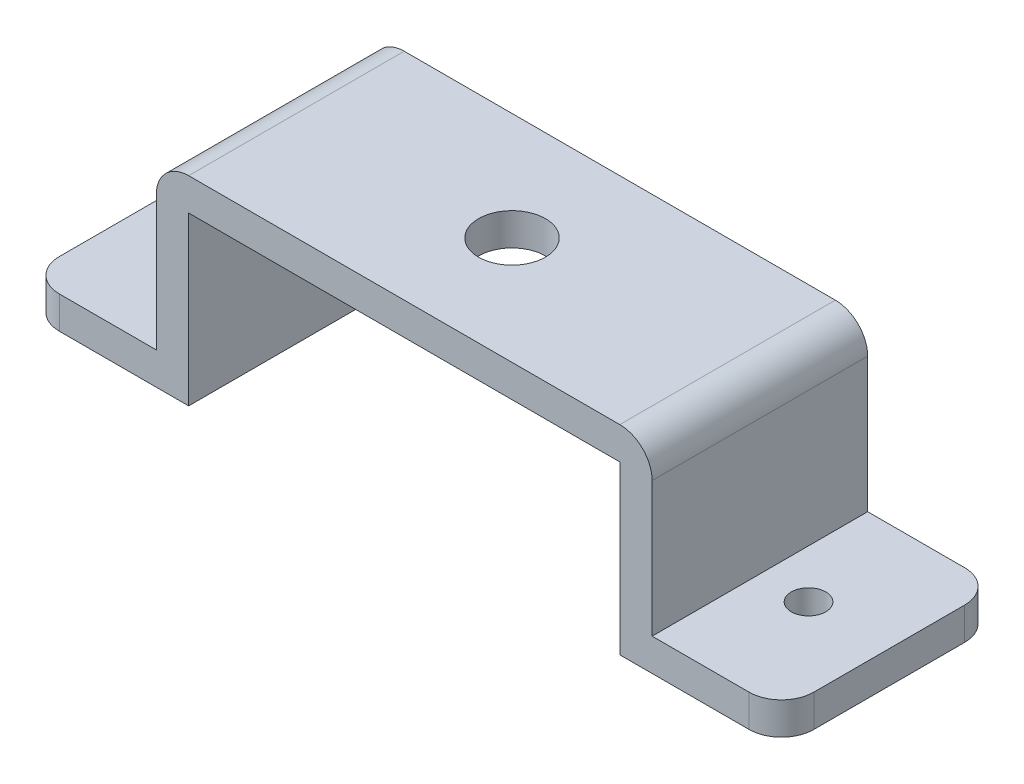
SolidWorks part; units mm, degrees
ref_plane "Front Plane" through (0, 0, 0) normal (0, 0, 1) x (1, 0, 0)
ref_plane "Top Plane" through (0, 0, 0) normal (0, 1, 0) x (1, 0, 0)
ref_plane "Right Plane" through (0, 0, 0) normal (1, 0, 0) x (0, 0, -1)
sketch "Sketch1" plane through (0, 0, 0) normal (0, 1, 0) x (1, 0, 0)
  line L1 (-35, -10) -> (35, -10)
  line L2 (-35, -10) -> (-35, 10)
  line L3 (-35, 10) -> (35, 10)
  line L4 (35, -10) -> (35, 10)
  line L5 (-35, -10) -> (35, 10) construction
  line L6 (-35, 10) -> (35, -10) construction
  point P0 (0, 0)
extrude "Boss-Extrude2" add sketch "Sketch1" along normal blind 3
sketch "Sketch3" plane through (0, 3, 0) normal (0, 1, 0) x (1, 0, 0)
  line L1 (35, 10) -> (-35, 10) construction
  line L2 (-35, -10) -> (35, -10) construction
  line L5 (20, -10) -> (20, 10)
  line L7 (-20, 10) -> (-20, -10)
  line L8 (-20, 10) -> (-23, 10)
  line L9 (-23, 10) -> (-23, -10)
  line L10 (-23, -10) -> (-20, -10)
  line L11 (20, 10) -> (23, 10)
  line L12 (23, 10) -> (23, -10)
  line L13 (23, -10) -> (20, -10)
extrude "Boss-Extrude3" add sketch "Sketch3" along normal blind 18
sketch "Sketch4" plane through (0, 21, 0) normal (0, 1, 0) x (1, 0, 0)
  line L1 (-23, 10) -> (23, 10)
  line L2 (-23, 10) -> (-23, -10)
  line L3 (-23, -10) -> (23, -10)
  line L4 (23, 10) -> (23, -10)
extrude "Boss-Extrude4" add sketch "Sketch4" along normal blind 3
sketch "Sketch5" plane through (0, 0, 10) normal (0, 0, 1) x (1, 0, 0)
  line L0 (-20, 3) -> (-20, 0)
  line L1 (-35, 0) -> (35, 0) construction
  line L3 (20, 3) -> (20, 0)
  line L4 (20, 0) -> (-20, 0)
  line L5 (-20, 3) -> (20, 3)
extrude "Cut-Extrude2" cut sketch "Sketch5" against normal through all
sketch "Sketch6" plane through (0, 21, 0) normal (0, -1, 0) x (1, 0, 0)
  circle A0 centre (0, 0) radius 3.1
extrude "Cut-Extrude3" cut sketch "Sketch6" against normal through all
fillet "Fillet2" radius 3 6 edges at (35, 1.5, -10) (35, 1.5, 10) (-35, 1.5, -10) (-35, 1.5, 10) (23, 24, 0) (-23, 24, 0)
sketch "Sketch7" plane through (0, 0, 0) normal (0, -1, 0) x (1, 0, 0)
  circle A0 centre (-27.4996, -0.0108) radius 1.6
  circle A1 centre (27.5004, -0.0108) radius 1.6
extrude "Cut-Extrude4" cut sketch "Sketch7" against normal through all
sketch "Sketch9" plane through (0, 0, 10) normal (0, 0, 1) x (1, 0, 0)
  line L3 (0, 15.5) -> (-23, 15.5)
  line L4 (-23, 21) -> (-23, 3) construction
  line L5 (-23, 15.5) -> (-23, 32.1713)
  line L6 (-23, 32.1713) -> (25.7271, 32.1713)
  line L7 (25.7271, 32.1713) -> (25.7271, 15.5)
  line L8 (25.7271, 15.5) -> (0, 15.5)
extrude "Cut-Extrude5" cut sketch "Sketch9" against normal blind 26 contours L3 L5 L6 L7 L8
sketch "Sketch10" plane through (0, 15.5, 0) normal (0, 1, 0) x (1, 0, 0)
  line L1 (-23, 10) -> (23, 10)
  line L2 (-23, 10) -> (-23, -10)
  line L3 (-23, -10) -> (23, -10)
  line L4 (23, 10) -> (23, -10)
extrude "Boss-Extrude5" add sketch "Sketch10" along normal blind 3
sketch "Sketch11" plane through (0, 18.5, 0) normal (0, 1, 0) x (1, 0, 0)
  circle A0 centre (0, 0) radius 3.1
extrude "Cut-Extrude6" cut sketch "Sketch11" against normal blind 3
fillet "Fillet3" radius 3 2 edges at (23, 18.5, 0) (-23, 18.5, 0)
